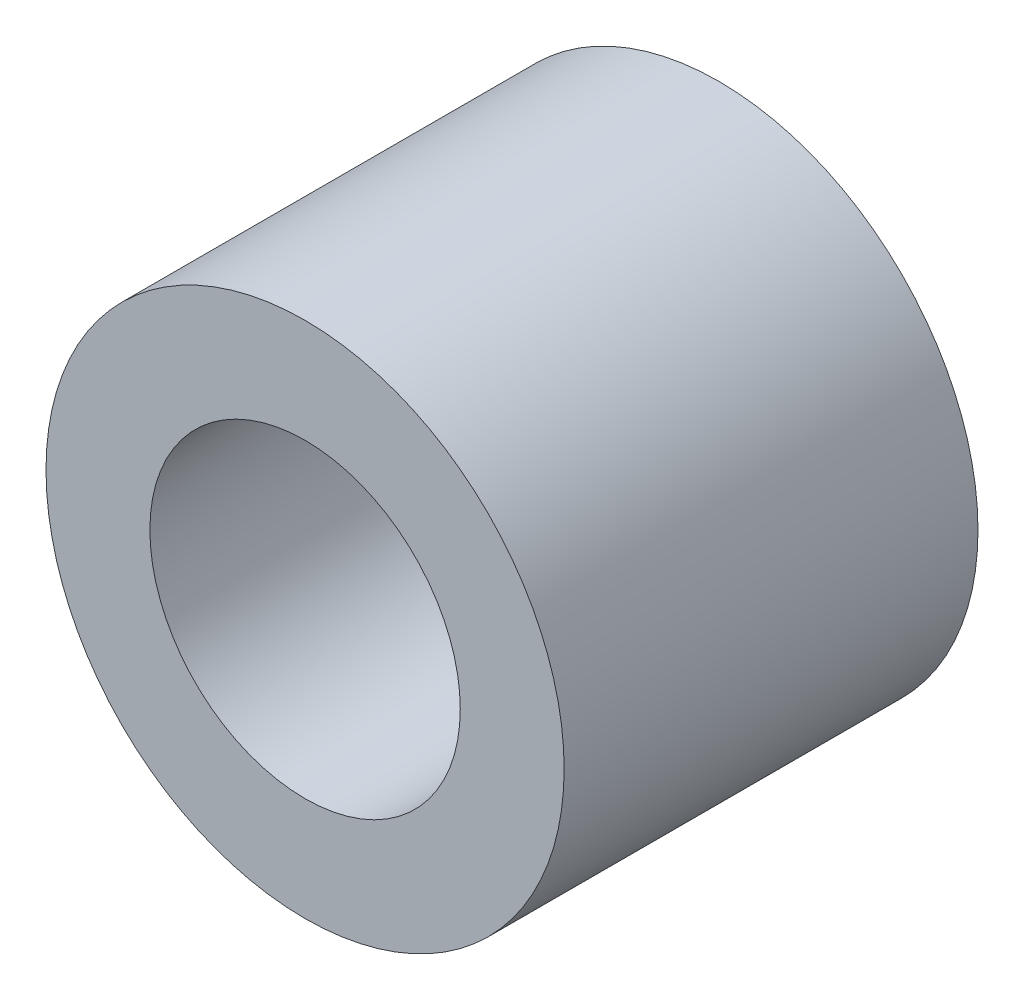
SolidWorks part; units mm, degrees
ref_plane "Front Plane" through (0, 0, 0) normal (0, 0, 1) x (1, 0, 0)
ref_plane "Top Plane" through (0, 0, 0) normal (0, 1, 0) x (1, 0, 0)
ref_plane "Right Plane" through (0, 0, 0) normal (1, 0, 0) x (0, 0, -1)
sketch "Sketch1" plane through (0, 0, 0) normal (0, 0, 1) x (1, 0, 0)
  circle A0 centre (0, 0) radius 7.9502
  circle A1 centre (0, 0) radius 4.7625
  dimension "OD" = 15.9004
  dimension "ID" = 9.525
sketch "Sketch2" plane through (0, 0, 0) normal (1, 0, 0) x (0, 0, -1)
  line L2 (6.35, 0) -> (-6.35, 0) construction
  line L4 (-6.35, -7.9502) -> (-6.35, 7.9502) construction
  line L5 (-6.35, -4.7625) -> (6.35, -4.7625)
  line L6 (6.35, 4.7625) -> (-6.35, 4.7625)
  line L7 (6.35, -7.9502) -> (6.35, 7.9502) construction
  line L8 (-6.35, 7.9502) -> (6.35, 7.9502) construction
  line L9 (-6.35, -7.9502) -> (6.35, -7.9502) construction
  line L10 (0, 7.9502) -> (0, -7.9502) construction
  line L11 (0, 4.7625) -> (0, -4.7625) construction
  point P4 (0, -4.7625)
  point P7 (0, 4.7625)
  point P8 (0, 0)
  point P12 (-6.35, 0)
  point P15 (6.35, 0)
  point P16 (0, -7.9502)
  point P17 (0, 7.9502)
  dimension "Length" = 12.7
sketch "Sketch5" plane through (0, 0, 0) normal (0, 0, 1) x (1, 0, 0)
  circle A1 centre (0, 0) radius 4.7625
  circle A2 centre (0, 0) radius 4.7625
  circle A3 centre (0, 0) radius 7.9502
  circle A4 centre (0, 0) radius 7.9502
  dimension "D1" = 0
  dimension "D2" = 0
extrude "Boss-Extrude1" add sketch "Sketch5" along normal up to vertex (6.35 mm away) and the other way up to vertex (6.35 mm away) up to point (0, 0, 6.35) other way up to point (0, 0, -6.35)
sketch "Sketch4" plane through (0, 0, 6.35) normal (0, 0, 1) x (1, 0, 0)
  line L0 (0, 0) -> (-3.3676, 3.3676)
  line L2 (0, -7.9502) -> (0, 7.9502) construction
  circle A1 centre (0, 0) radius 4.7625 construction
  dimension "D1" = 45
equation "\"D1\"= \"Length@Sketch2\""
